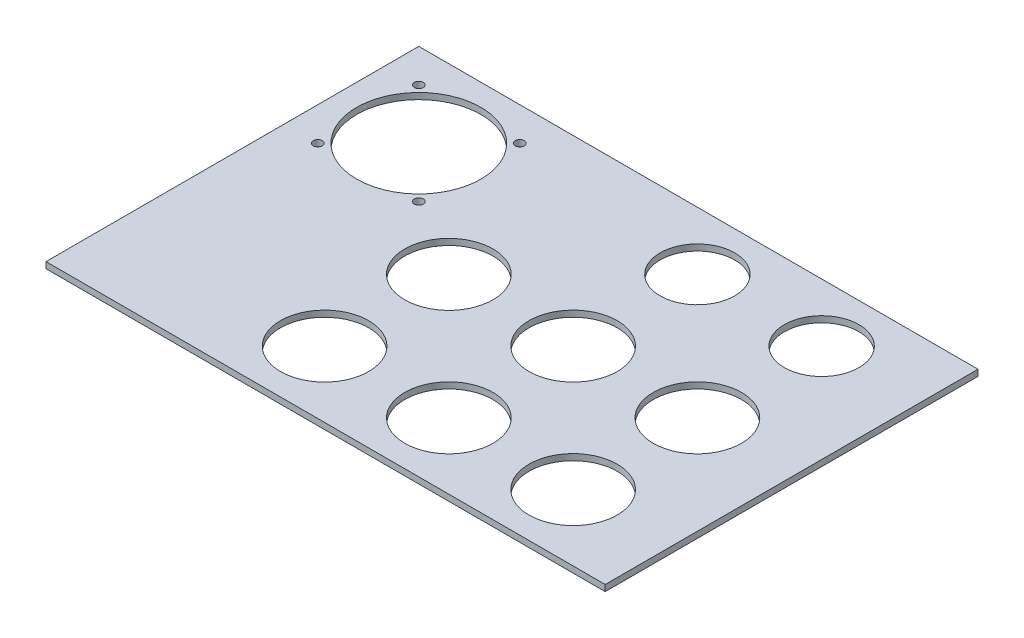
SolidWorks part; units mm, degrees
ref_plane "Front Plane" through (0, 0, 0) normal (0, 0, 1) x (1, 0, 0)
ref_plane "Top Plane" through (0, 0, 0) normal (0, 1, 0) x (1, 0, 0)
ref_plane "Right Plane" through (0, 0, 0) normal (1, 0, 0) x (0, 0, -1)
sketch "Sketch1" plane through (0, 0, 0) normal (0, 1, 0) x (1, 0, 0)
  line L1 (-118.7285, 78.6755) -> (61.2715, 78.6755)
  line L2 (-118.7285, 78.6755) -> (-118.7285, -41.3245)
  line L3 (-118.7285, -41.3245) -> (61.2715, -41.3245)
  line L4 (61.2715, 78.6755) -> (61.2715, -41.3245)
  dimension "D1" = 180
  dimension "D2" = 120
extrude "Boss-Extrude1" add sketch "Sketch1" along normal blind 2
sketch "Sketch2" plane through (0, 2, 0) normal (0, 1, 0) x (1, 0, 0)
  line L0 (-50.338, -20.0414) -> (-50.338, 19.9586) construction
  line L1 (-118.7285, 78.6755) -> (-118.7285, -41.3245) construction
  line L2 (61.2715, 78.6755) -> (-118.7285, 78.6755) construction
  circle A0 centre (-50.338, -20.0414) radius 14.2
  circle A5 centre (29.662, 59.9586) radius 12
  circle A6 centre (-10.338, 59.9586) radius 12
  circle A7 centre (-10.338, -20.0414) radius 14.2
  circle A8 centre (29.662, -20.0414) radius 14.2
  circle A10 centre (-50.338, 19.9586) radius 14.2
  circle A11 centre (-10.338, 19.9586) radius 14.2
  circle A12 centre (29.662, 19.9586) radius 14.2
  circle A13 centre (-91.7285, 51.6755) radius 20.01
  dimension "D1" = 28.4
  dimension "D2" = 24
  dimension "D3" = 40
  dimension "D4" = 3
  dimension "D5" = 40.02
  dimension "D9" = 27
  dimension "D6" = 40
  dimension "D7" = 2
  dimension "D8" = 40
  dimension "D10" = 27
extrude "button_holes_cut" cut sketch "Sketch2" against normal up to next
sketch "speaker_bolt_holes" plane through (0, 2, 0) normal (0, 1, 0) x (1, 0, 0)
  line L1 (-107.9785, 67.9255) -> (-75.4785, 67.9255) construction
  line L2 (-107.9785, 67.9255) -> (-107.9785, 35.4255) construction
  line L3 (-107.9785, 35.4255) -> (-75.4785, 35.4255) construction
  line L4 (-75.4785, 67.9255) -> (-75.4785, 35.4255) construction
  line L5 (-107.9785, 67.9255) -> (-75.4785, 35.4255) construction
  line L6 (-107.9785, 35.4255) -> (-75.4785, 67.9255) construction
  circle A2 centre (-91.7285, 51.6755) radius 20.01 construction
  point P0 (-91.7285, 51.6755)
  point P8 (-75.4785, 67.9255)
  point P9 (-107.9785, 67.9255)
  point P10 (-75.4785, 35.4255)
  point P11 (-107.9785, 35.4255)
  point P13 (-91.7285, 51.6755)
  dimension "D1" = 32.5
hole_wizard "M2.5 Clearance Hole1" positions "speaker_bolt_holes" profile "Sketch7" hole size "M2.5" standard "DIN" end condition through all
sketch "Sketch7" plane through (-91.7285, 2, -51.6755) normal (1, 0, 0) x (0, 0, 1)
  line L0 (0, 0) -> (0, 2)
  line L1 (0, 2) -> (1.45, 2)
  line L2 (1.45, 2) -> (1.45, 0)
  line L5 (1.45, 0) -> (0, 0)
  line L11 (0, -6.35) -> (0, 107.95) construction
  dimension "Thru Hole Dia." = 2.9
  dimension "Thru Hole Depth" = 2
